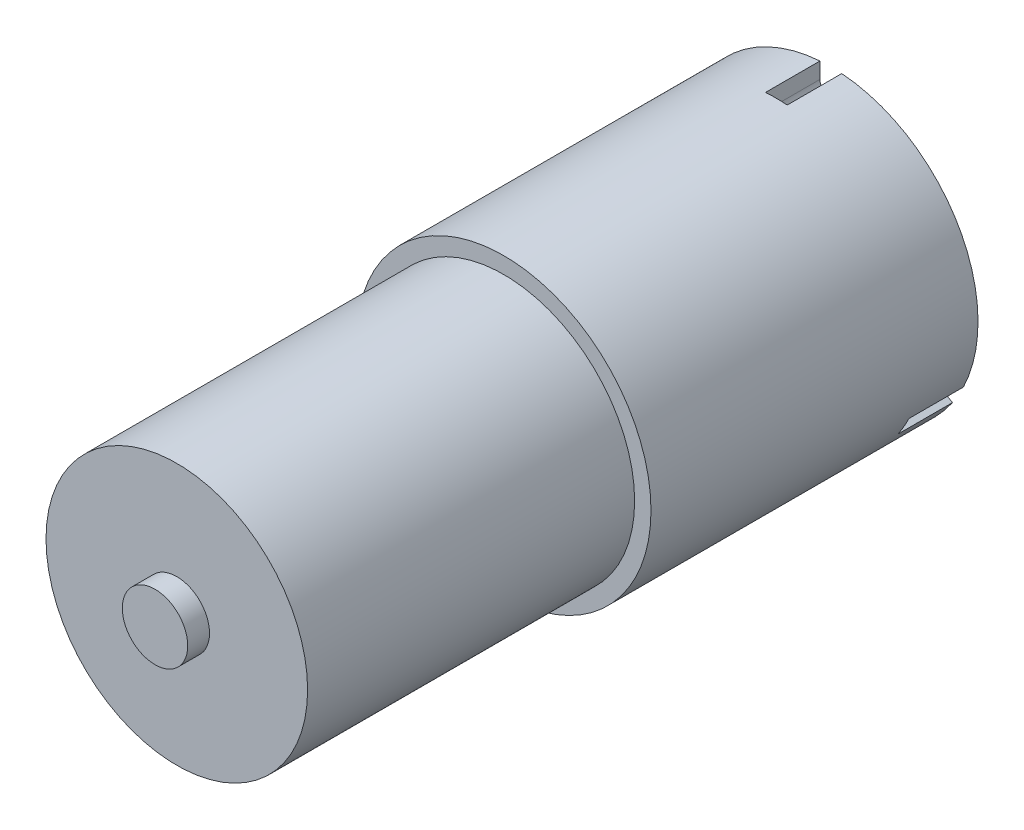
SolidWorks part; units mm, degrees
material "热轧扁钢 Q235A"
ref_plane "前视基准面" through (0, 0, 0) normal (0, 0, 1) x (1, 0, 0)
ref_plane "上视基准面" through (0, 0, 0) normal (0, 1, 0) x (1, 0, 0)
ref_plane "右视基准面" through (0, 0, 0) normal (1, 0, 0) x (0, 0, -1)
sketch "草图1" plane through (0, 0, 0) normal (0, 0, 1) x (1, 0, 0)
  circle A0 centre (0, 0) radius 13.5
  dimension "D1" = 27
extrude "凸台-拉伸1" add sketch "草图1" along normal blind 30
sketch "草图2" plane through (0, 0, 30) normal (0, 0, 1) x (1, 0, 0)
  circle A0 centre (0, 0) radius 12
  dimension "D1" = 24
extrude "凸台-拉伸2" add sketch "草图2" along normal blind 30
sketch "草图3" plane through (0, 0, 60) normal (0, 0, 1) x (1, 0, 0)
  circle A0 centre (0, 0) radius 3
  dimension "D1" = 6
extrude "凸台-拉伸3" add sketch "草图3" along normal blind 2
sketch "草图4" plane through (0, 0, 0) normal (0, 0, -1) x (-1, 0, 0)
  line L0 (0, 14.8277) -> (0, 0) construction
  line L1 (-1, 12) -> (-1, 13.9787)
  line L2 (-1, 13.9787) -> (1, 13.9787)
  line L3 (1, 13.9787) -> (1, 12)
  line L4 (10.8923, -5.134) -> (12.6059, -6.1233)
  line L5 (12.6059, -6.1233) -> (11.6059, -7.8554)
  line L6 (11.6059, -7.8554) -> (9.8923, -6.866)
  line L7 (-9.8923, -6.866) -> (-11.6059, -7.8554)
  line L8 (-11.6059, -7.8554) -> (-12.6059, -6.1233)
  line L9 (-12.6059, -6.1233) -> (-10.8923, -5.134)
  arc A0 (-1, 12) -> (1, 12) centre (0, 12) ccw
  arc A1 (10.8923, -5.134) -> (9.8923, -6.866) centre (10.3923, -6) ccw
  arc A2 (-9.8923, -6.866) -> (-10.8923, -5.134) centre (-10.3923, -6) ccw
  point P20 (0, 0)
  dimension "D1" = 2
  dimension "D2" = 12
  dimension "D3" = 3
extrude "切除-拉伸1" cut sketch "草图4" against normal blind 5
sketch "草图5" plane through (0, 0, 0) normal (0, 0, -1) x (-1, 0, 0)
  circle A0 centre (0, 0) radius 1.25
  circle A1 centre (6, 0) radius 1.25
  dimension "D1" = 2.5
  dimension "D2" = 2.5
  dimension "D3" = 6
extrude "凸台-拉伸4" add sketch "草图5" along normal blind 5
fillet "圆角1" radius 0.5 2 edges at (-1.25, 0, -5) (-7.25, 0, -5)
